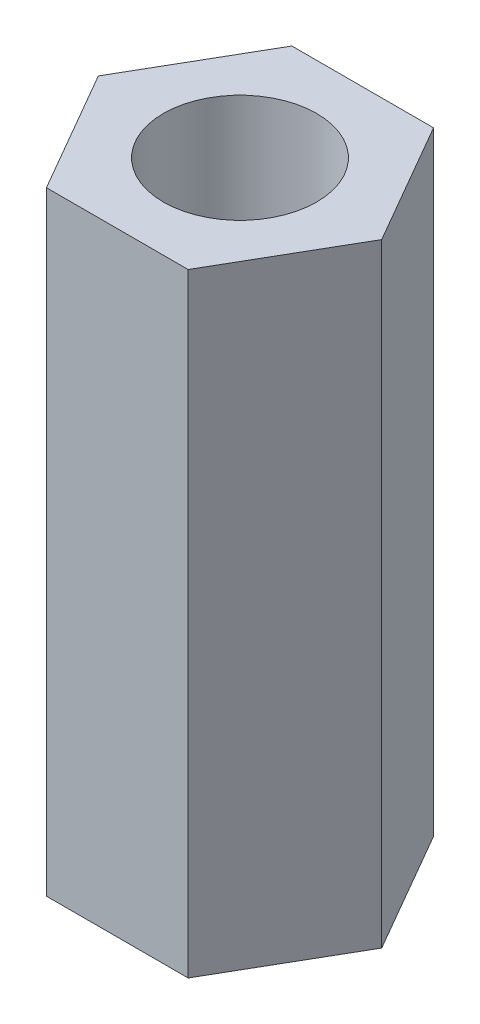
SolidWorks part; units mm, degrees
ref_plane "前视基准面" through (0, 0, 0) normal (0, 0, 1) x (1, 0, 0)
ref_plane "上视基准面" through (0, 0, 0) normal (0, 1, 0) x (1, 0, 0)
ref_plane "右视基准面" through (0, 0, 0) normal (1, 0, 0) x (0, 0, -1)
other "Configuration Table"
sketch "草图1" plane through (0, 0, 0) normal (0, 1, 0) x (1, 0, 0)
  line L1 (1.1547, 2) -> (-1.1547, 2)
  line L2 (-1.1547, 2) -> (-2.3094, 0)
  line L3 (-2.3094, 0) -> (-1.1547, -2)
  line L4 (-1.1547, -2) -> (1.1547, -2)
  line L5 (1.1547, -2) -> (2.3094, 0)
  line L6 (2.3094, 0) -> (1.1547, 2)
  circle A0 centre (0, 0) radius 2 construction
  circle A1 centre (0, 0) radius 1.25
  dimension "D2" = 2.5
  dimension "D1" = 4
extrude "凸台-拉伸1" add sketch "草图1" along normal blind 10
